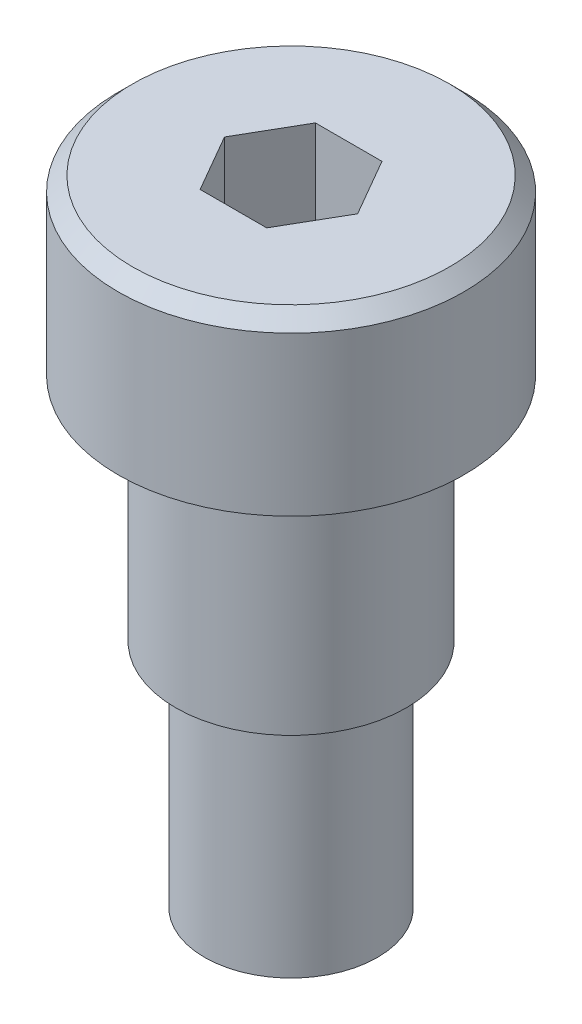
SolidWorks part; units mm, degrees
material "AISI 304"
ref_plane "Front Plane" through (0, 0, 0) normal (0, 0, 1) x (1, 0, 0)
ref_plane "Top Plane" through (0, 0, 0) normal (0, 1, 0) x (1, 0, 0)
ref_plane "Right Plane" through (0, 0, 0) normal (1, 0, 0) x (0, 0, -1)
sketch "Sketch1" plane through (0, 0, 0) normal (0, 1, 0) x (1, 0, 0)
  circle A0 centre (0, 0) radius 3
  dimension "D1" = 6
extrude "Boss-Extrude1" add sketch "Sketch1" along normal blind 3
sketch "Sketch2" plane through (0, 0, 0) normal (0, -1, 0) x (1, 0, 0)
  circle A0 centre (0, 0) radius 2
  dimension "D1" = 4
extrude "Boss-Extrude2" add sketch "Sketch2" along normal blind 4
sketch "Sketch3" plane through (0, -4, 0) normal (0, -1, 0) x (1, 0, 0)
  circle A0 centre (0, 0) radius 1.5
  dimension "D1" = 3
extrude "Boss-Extrude3" add sketch "Sketch3" along normal blind 4
cosmetic thread "Cosmetic Thread1" parameters "D2"=2.439
sketch "Sketch4" plane through (0, 3, 0) normal (0, 1, 0) x (1, 0, 0)
  line L1 (0.5774, 1) -> (-0.5774, 1)
  line L2 (-0.5774, 1) -> (-1.1547, 0)
  line L3 (-1.1547, 0) -> (-0.5774, -1)
  line L4 (-0.5774, -1) -> (0.5774, -1)
  line L5 (0.5774, -1) -> (1.1547, 0)
  line L6 (1.1547, 0) -> (0.5774, 1)
  circle A0 centre (0, 0) radius 1 construction
  dimension "D1" = 2
extrude "Cut-Extrude1" cut sketch "Sketch4" against normal blind 2
chamfer "Chamfer1" distance 0.25 angle 45 1 edges at (0, 3, 3)
